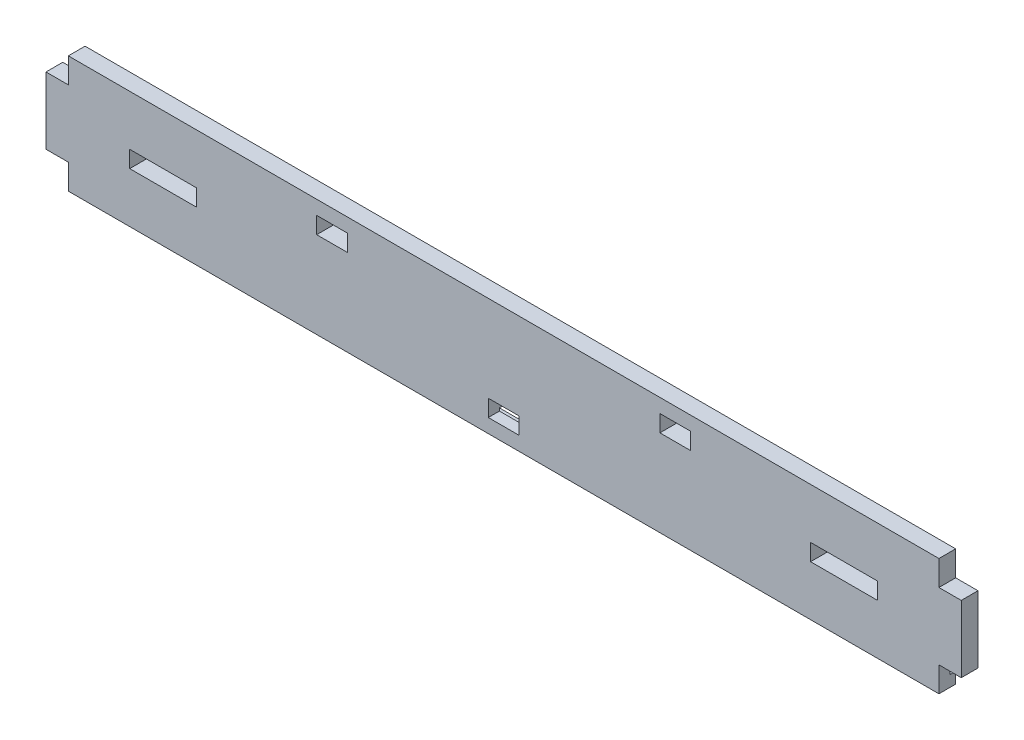
SolidWorks part; units mm, degrees
ref_plane "Front Plane" through (0, 0, 0) normal (0, 0, 1) x (1, 0, 0)
ref_plane "Top Plane" through (0, 0, 0) normal (0, 1, 0) x (1, 0, 0)
ref_plane "Right Plane" through (0, 0, 0) normal (1, 0, 0) x (0, 0, -1)
sketch "Sketch1" plane through (0, 0, 0) normal (1, 0, 0) x (0, 0, -1)
  line L0 (-292.4077, 79.6742) -> (-292.4077, 155.8742) construction
  line L1 (-311.4577, 184.4492) -> (-292.4077, 184.4492)
  line L2 (-311.4577, 184.4492) -> (-311.4577, 51.0992)
  line L3 (-311.4577, 51.0992) -> (-292.4077, 51.0992)
  line L4 (-292.4077, 184.4492) -> (-292.4077, 51.0992)
  dimension "D1" = 133.35
  dimension "D2" = 19.05
extrude "Boss-Extrude1" add sketch "Sketch1" against normal blind 1041.4
sketch "Sketch2" plane through (0, 0, 311.4577) normal (0, 0, 1) x (1, 0, 0)
  line L0 (-520.7, 184.4492) -> (-520.7, 51.0992) construction
  line L1 (-869.95, 127.2992) -> (-946.15, 127.2992)
  line L2 (-869.95, 127.2992) -> (-869.95, 108.2492)
  line L3 (-869.95, 108.2492) -> (-946.15, 108.2492)
  line L4 (-946.15, 127.2992) -> (-946.15, 108.2492)
  line L5 (-1041.4, 184.4492) -> (0, 184.4492) construction
  line L6 (-1041.4, 51.0992) -> (0, 51.0992) construction
  line L7 (-1041.4, 184.4492) -> (-1041.4, 51.0992) construction
  line L8 (-908.05, 184.4492) -> (-908.05, 127.2992) construction
  line L9 (-908.05, 127.2992) -> (-908.05, 108.2492) construction
  line L10 (-908.05, 108.2492) -> (-908.05, 51.0992) construction
  line L11 (-171.45, 127.2992) -> (-171.45, 108.2492)
  line L12 (-171.45, 127.2992) -> (-95.25, 127.2992)
  line L13 (-95.25, 127.2992) -> (-95.25, 108.2492)
  line L14 (-171.45, 108.2492) -> (-95.25, 108.2492)
  line L15 (-342.9, 168.5615) -> (-342.9, 149.5115)
  line L16 (-733.425, 168.5615) -> (-698.5, 168.5615)
  line L17 (-733.425, 168.5615) -> (-733.425, 149.5115)
  line L18 (-733.425, 149.5115) -> (-698.5, 149.5115)
  line L19 (-698.5, 168.5615) -> (-698.5, 149.5115)
  line L20 (-307.975, 149.5115) -> (-342.9, 149.5115)
  line L21 (-307.975, 168.5615) -> (-307.975, 149.5115)
  line L22 (-307.975, 168.5615) -> (-342.9, 168.5615)
  line L23 (0, 184.4492) -> (-25.4, 184.4492)
  line L24 (-1041.4, 184.4492) -> (-1016, 184.4492)
  line L25 (-1041.4, 184.4492) -> (-1041.4, 155.8742)
  line L26 (-1041.4, 155.8742) -> (-1016, 155.8742)
  line L27 (-1016, 184.4492) -> (-1016, 155.8742)
  line L28 (0, 184.4492) -> (0, 155.8742)
  line L29 (0, 155.8742) -> (-25.4, 155.8742)
  line L30 (-25.4, 184.4492) -> (-25.4, 155.8742)
  line L31 (-946.15, 117.7742) -> (-998.7307, 117.7742) construction
  line L32 (-538.1625, 66.9742) -> (-503.2375, 66.9742)
  line L33 (-538.1625, 66.9742) -> (-538.1625, 86.0242)
  line L34 (-538.1625, 86.0242) -> (-503.2375, 86.0242)
  line L35 (-503.2375, 66.9742) -> (-503.2375, 86.0242)
  line L36 (-538.1625, 66.9742) -> (-503.2375, 86.0242) construction
  line L37 (-538.1625, 86.0242) -> (-503.2375, 66.9742) construction
  line L38 (-1041.4, 51.0992) -> (-1041.4, 79.6742)
  line L39 (-1041.4, 51.0992) -> (-1016, 51.0992)
  line L40 (-1016, 51.0992) -> (-1016, 79.6742)
  line L41 (-1041.4, 79.6742) -> (-1016, 79.6742)
  line L42 (0, 51.0992) -> (0, 79.6742)
  line L43 (0, 51.0992) -> (-25.4, 51.0992)
  line L44 (-25.4, 51.0992) -> (-25.4, 79.6742)
  line L45 (0, 79.6742) -> (-25.4, 79.6742)
  point P37 (-520.7, 76.4992)
  dimension "D1" = 76.2
  dimension "D2" = 19.05
  dimension "D3" = 95.25
  dimension "D4" = 177.8
  dimension "D5" = 34.925
  dimension "D6" = 15.8877
  dimension "D7" = 19.05
  dimension "D8" = 25.4
  dimension "D9" = 28.575
  dimension "D10" = 19.05
  dimension "D11" = 34.925
  dimension "D12" = 15.875
extrude "Cut-Extrude1" cut sketch "Sketch2" against normal through all
sketch "Sketch3" plane through (-1041.4, 0, 0) normal (-1, 0, 0) x (0, 0, 1)
  line L0 (292.4077, 79.6742) -> (292.4077, 155.8742) construction
  line L1 (292.4077, 70.1492) -> (298.7577, 70.1492)
  line L2 (292.4077, 70.1492) -> (292.4077, 63.7992)
  line L3 (292.4077, 63.7992) -> (298.7577, 63.7992)
  line L4 (298.7577, 70.1492) -> (298.7577, 63.7992)
  line L5 (311.4577, 51.0992) -> (292.4077, 51.0992) construction
  dimension "D1" = 6.35
  dimension "D2" = 12.7
  dimension "D3" = 6.35
extrude "Cut-Extrude2" cut sketch "Sketch3" against normal through all
